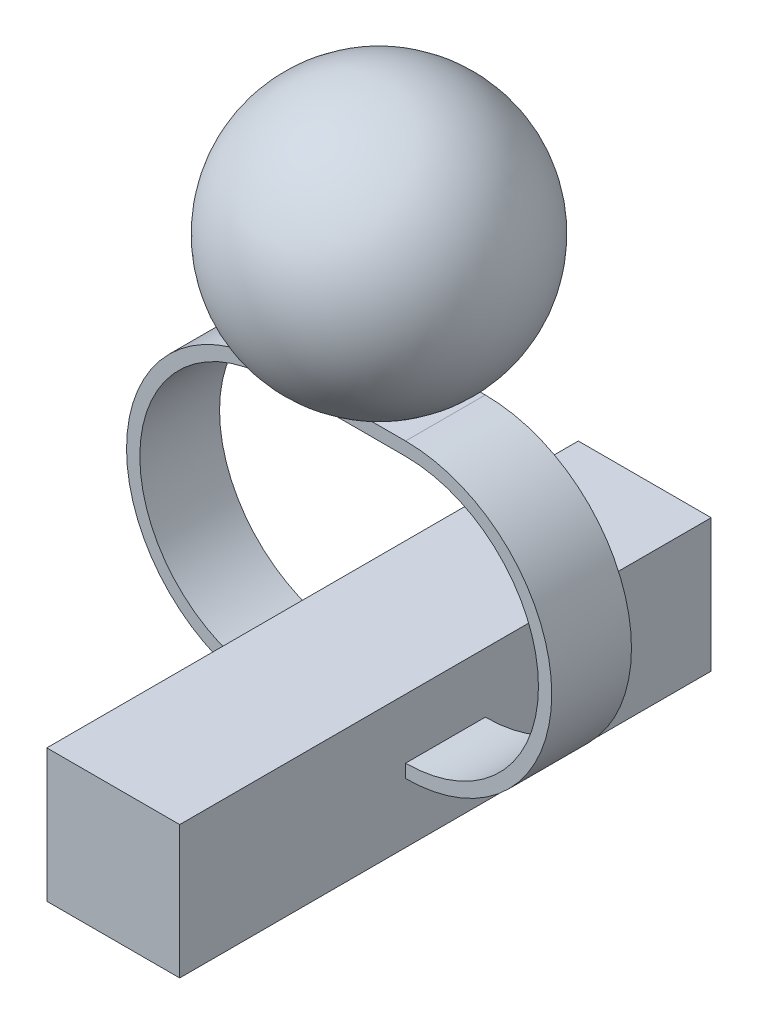
SolidWorks part; units mm, degrees
ref_plane "Front Plane" through (0, 0, 0) normal (0, 0, 1) x (1, 0, 0)
ref_plane "Top Plane" through (0, 0, 0) normal (0, 1, 0) x (1, 0, 0)
ref_plane "Right Plane" through (0, 0, 0) normal (1, 0, 0) x (0, 0, -1)
sketch "Sketch1" plane through (0, 0, 0) normal (0, 0, 1) x (1, 0, 0)
  line L1 (-2.5, 2.5) -> (2.5, 2.5)
  line L2 (-2.5, 2.5) -> (-2.5, -2.5)
  line L3 (-2.5, -2.5) -> (2.5, -2.5)
  line L4 (2.5, 2.5) -> (2.5, -2.5)
  line L5 (-2.5, 2.5) -> (2.5, -2.5) construction
  line L6 (-2.5, -2.5) -> (2.5, 2.5) construction
  point P0 (0, 0)
  dimension "D1" = 5
  dimension "D2" = 5
extrude "Boss-Extrude1" add sketch "Sketch1" along normal mid plane 20
sketch "Sketch2" plane through (0, 0, 0) normal (0, 0, 1) x (1, 0, 0)
  line L0 (-2.5, 0) -> (2.5, 0) construction
  line L1 (-2.5, 2.5) -> (-2.5, -2.5) construction
  line L2 (2.5, -2.5) -> (2.5, 2.5) construction
  line L3 (0, 0.25) -> (-2.5, 0.25)
  line L4 (-2.5, 10.25) -> (0, 10.25)
  line L5 (0, -0.25) -> (-2.5, -0.25)
  line L6 (-2.5, 10.75) -> (0, 10.75)
  line L7 (0, 0.25) -> (0, -0.25)
  line L8 (0, 10.75) -> (0, 10.25)
  arc A0 (-2.5, 0.25) -> (-2.5, 10.25) centre (-2.5, 5.25) cw
  arc A1 (-2.5, -0.25) -> (-2.5, 10.75) centre (-2.5, 5.25) cw
  point P11 (0, 0)
  dimension "D1" = 5
  dimension "t" = 0.5
extrude "Boss-Extrude2" add sketch "Sketch2" along normal mid plane 3
mirror "Mirror1" about plane through (0, 0, 0) normal (1, 0, 0) of "Boss-Extrude2"
sketch "Sketch3" plane through (0, 0, 0) normal (0, 0, 1) x (1, 0, 0)
  line L0 (0, 0) -> (0, 19.3848) construction
  line L1 (2.5, 10.75) -> (-2.5, 10.75) construction
  line L2 (0, 10.5) -> (0, 20.5)
  arc A0 (0, 20.5) -> (0, 10.5) centre (0, 15.5) ccw
  dimension "D1" = 10
  dimension "D2" = 4.75
revolve "Revolve3" add sketch "Sketch3" angle 360 about L0
equation "\"a\"= 5mm'Dimenzija nosilca"
equation "\"w\" = 3mm'Širina vzmeti"
equation "\"t\"= 0.5mm'Debelina vzmeti"
equation "\"r\"= 5mm'Polmer loka vmzeti"
equation "\"rr\"= 10mm'Polmer resonatorja"
equation "\"L\" = 20mm'Dolžina bazne celice"
equation "\"t@Sketch2\"=\"t\""
equation "\"D1@Sketch2\"=\"r\""
equation "\"D1@Sketch1\"=\"a\""
equation "\"D2@Sketch1\"=\"a\""
equation "\"D1@Boss-Extrude1\"=\"L\""
equation "\"D1@Sketch3\"=\"rr\""
equation "\"D2@Sketch3\"=\"r\"-\"t\"/2"
